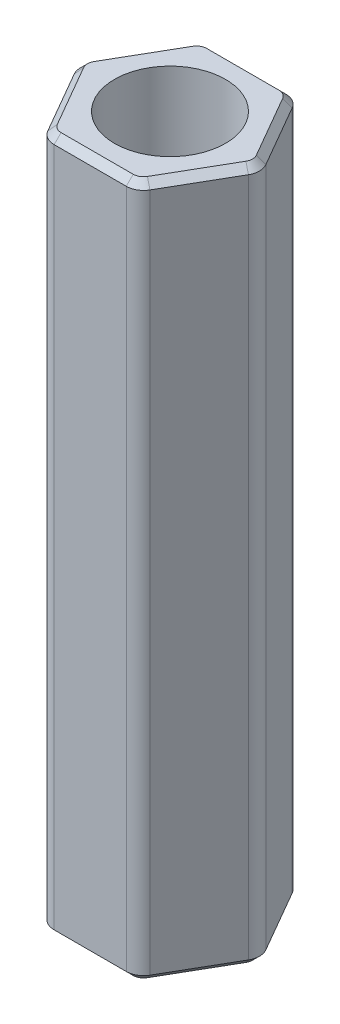
SolidWorks part; units mm, degrees
ref_plane "Front Plane" through (0, 0, 0) normal (0, 0, 1) x (1, 0, 0)
ref_plane "Top Plane" through (0, 0, 0) normal (0, 1, 0) x (1, 0, 0)
ref_plane "Right Plane" through (0, 0, 0) normal (1, 0, 0) x (0, 0, -1)
other "Configuration Table"
sketch "Sketch1" plane through (0, 0, 0) normal (0, 1, 0) x (1, 0, 0)
  line L1 (1.3279, -2.3) -> (2.6558, 0)
  line L2 (2.6558, 0) -> (1.3279, 2.3)
  line L3 (1.3279, 2.3) -> (-1.3279, 2.3)
  line L4 (-1.3279, 2.3) -> (-2.6558, 0)
  line L5 (-2.6558, 0) -> (-1.3279, -2.3)
  line L6 (-1.3279, -2.3) -> (1.3279, -2.3)
  circle A0 centre (0, 0) radius 2.3 construction
  dimension "D1" = 4.6
extrude "Boss-Extrude1" add sketch "Sketch1" along normal blind 20
sketch "Sketch2" plane through (0, 20, 0) normal (0, 1, 0) x (1, 0, 0)
  circle A0 centre (0, 0) radius 1.6
  dimension "D1" = 3.2
extrude "Cut-Extrude1" cut sketch "Sketch2" against normal through all
fillet "Fillet1" radius 0.5 6 edges at (-1.3279, 10, 2.3) (-2.6558, 10, 0) (-1.3279, 10, -2.3) (1.3279, 10, -2.3) (2.6558, 10, 0) (1.3279, 10, 2.3)
chamfer "Chamfer1" distance 0.2 angle 45 24 edges at (-1.2892, 0, 2.233) (-1.9919, 0, 1.15) (0, 0, 2.3) (-2.5785, 0, 0) (1.2892, 0, 2.233) (-1.9919, 0, -1.15) (1.9919, 0, 1.15) (-1.2892, 0, -2.233) (2.5785, 0, 0) (0, 0, -2.3) (1.9919, 0, -1.15) (1.2892, 0, -2.233) (0, 20, -2.3) (-1.9919, 20, 1.15) (-1.2892, 20, 2.233) (-2.5785, 20, 0) (0, 20, 2.3) (-1.9919, 20, -1.15) (1.2892, 20, 2.233) (-1.2892, 20, -2.233) (1.9919, 20, 1.15) (2.5785, 20, 0) (1.2892, 20, -2.233) (1.9919, 20, -1.15)
